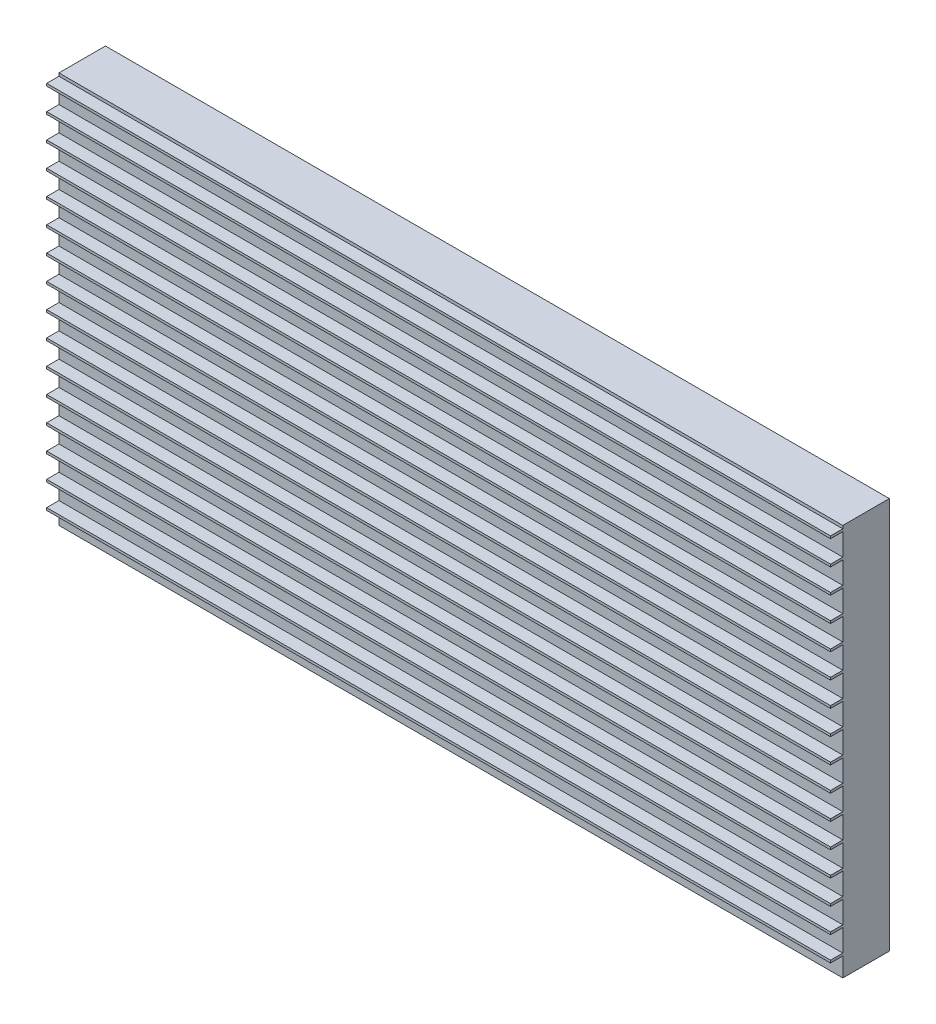
SolidWorks part; units mm, degrees
material "ABS"
ref_plane "Front Plane" through (0, 0, 0) normal (0, 0, 1) x (1, 0, 0)
ref_plane "Top Plane" through (0, 0, 0) normal (0, 1, 0) x (1, 0, 0)
ref_plane "Right Plane" through (0, 0, 0) normal (1, 0, 0) x (0, 0, -1)
sketch "Sketch1" plane through (0, 0, 0) normal (0, 0, 1) x (1, 0, 0)
  line L0 (0, 80) -> (0, 0) construction
  line L1 (-160, 80) -> (160, 80)
  line L2 (-160, 80) -> (-160, -80)
  line L3 (-160, -80) -> (160, -80)
  line L4 (160, 80) -> (160, -80)
  line L5 (0, 0) -> (0, -80) construction
  dimension "D1" = 320
  dimension "D2" = 160
extrude "Boss-Extrude1" add sketch "Sketch1" along normal blind 19
sketch "Sketch2" plane through (0, 0, 19) normal (0, 0, 1) x (1, 0, 0)
  line L0 (-155, 80) -> (-155, 75) construction
  line L1 (160, 80) -> (-160, 80) construction
  line L2 (-155, 75) -> (-160, 75) construction
  line L3 (-160, 80) -> (-160, -80) construction
  circle A0 centre (-155, 75) radius 2.5
  dimension "D1" = 5
  dimension "D2" = 5
extrude "Boss-Extrude2" [suppressed] add sketch "Sketch2" along normal blind 5
fillet "Fillet1" [suppressed] radius 2.5
pattern_linear "LPattern1" [suppressed] count 32 spacing 10 count 16 spacing 10
sketch "Sketch4" plane through (0, 0, 19) normal (0, 0, 1) x (1, 0, 0)
  line L0 (-160, 80) -> (-160, -80) construction
  line L1 (-160, 78.8) -> (160, 78.8)
  line L2 (-160, 78.8) -> (-160, 77.8)
  line L3 (-160, 77.8) -> (160, 77.8)
  line L4 (160, 78.8) -> (160, 77.8)
  line L5 (160, -80) -> (160, 80) construction
  line L6 (160, 80) -> (-160, 80) construction
  dimension "D1" = 1
  dimension "D2" = 1.2
extrude "Boss-Extrude4" add sketch "Sketch4" along normal blind 5
pattern_linear "LPattern2" count 16 spacing 10 along (0, -1, 0) of "Boss-Extrude4"
sketch "Sketch3" plane through (0, 0, 0) normal (0, 0, -1) x (-1, 0, 0)
  line L0 (-160, -80) -> (-160, 80) construction
  line L1 (-146.5, 40) -> (146.5, 40) construction
  line L2 (-146.5, 40) -> (-146.5, -40) construction
  line L3 (-146.5, -40) -> (146.5, -40) construction
  line L4 (146.5, 40) -> (146.5, -40) construction
  line L5 (0, 40) -> (0, 0) construction
  line L6 (0, 0) -> (0, -40) construction
  circle A0 centre (-146.5, 40) radius 1.5
  circle A1 centre (-146.5, -40) radius 1.5
  circle A2 centre (146.5, 40) radius 1.5
  circle A3 centre (146.5, -40) radius 1.5
  dimension "D1" = 3
  dimension "D2" = 80
  dimension "D3" = 13.5
extrude "Boss-Extrude3" [suppressed] add sketch "Sketch3" along normal blind 5
sketch "Sketch5" plane through (0, 0, 0) normal (0, 0, -1) x (-1, 0, 0)
  line L0 (-5, 0) -> (0, 0) construction
  line L1 (-140, 60) -> (-5, 60)
  line L2 (-140, 60) -> (-140, -60)
  line L3 (-140, -60) -> (-5, -60)
  line L4 (-5, 60) -> (-5, -60)
  line L5 (5, 60) -> (140, 60)
  line L6 (5, 60) -> (5, -60)
  line L7 (5, -60) -> (140, -60)
  line L8 (140, 60) -> (140, -60)
  line L9 (0, 0) -> (5, 0) construction
  dimension "D1" = 120
  dimension "D2" = 135
  dimension "D3" = 20
extrude "Cut-Extrude1" cut sketch "Sketch5" against normal blind 12
sketch "Sketch6" plane through (0, 0, 0) normal (0, 0, -1) x (-1, 0, 0)
  line L0 (0, 0) -> (0, 66.25) construction
  line L1 (-143.75, 50) -> (143.75, 50) construction
  line L2 (-143.75, 50) -> (-143.75, -50) construction
  line L3 (-143.75, -50) -> (143.75, -50) construction
  line L4 (143.75, 50) -> (143.75, -50) construction
  line L5 (0, 0) -> (0, -66.25) construction
  line L6 (-143.75, 0) -> (0, 0) construction
  line L7 (143.75, 0) -> (0, 0) construction
  line L8 (0, 66.25) -> (0, 80) construction
  line L9 (-160, 80) -> (160, 80) construction
  line L11 (-160, -80) -> (-160, 80) construction
  line L12 (-143.75, 50) -> (-140, 50) construction
  line L13 (-140, 60) -> (-140, -60) construction
  line L14 (0, -66.25) -> (0, -80) construction
  line L15 (160, -80) -> (-160, -80) construction
  line L16 (-143.75, -50) -> (-160, -50) construction
  circle A0 centre (-143.75, 50) radius 2
  circle A1 centre (-143.75, -50) radius 2
  circle A2 centre (0, 66.25) radius 2
  circle A3 centre (143.75, 50) radius 2
  circle A4 centre (143.75, -50) radius 2
  circle A5 centre (0, -66.25) radius 2
  dimension "D1" = 4
  dimension "D2" = 100
  dimension "D3" = 132.5
  dimension "D4" = 16.25
  dimension "D5" = 16.25
  dimension "D6" = 287.5
extrude "Cut-Extrude2" cut sketch "Sketch6" against normal blind 12
sketch "Sketch7" plane through (0, 0, 0) normal (0, 0, -1) x (-1, 0, 0)
  line L0 (0, 66) -> (0, 0) construction
  line L1 (-120, 66) -> (120, 66) construction
  line L2 (-120, 66) -> (-120, -66) construction
  line L3 (-120, -66) -> (120, -66) construction
  line L4 (120, 66) -> (120, -66) construction
  line L5 (0, 0) -> (0, -66) construction
  line L6 (160, -80) -> (-160, -80) construction
  line L7 (-160, -80) -> (-160, 80) construction
  circle A0 centre (-120, 66) radius 1.5
  circle A1 centre (120, 66) radius 1.5
  circle A2 centre (120, -66) radius 1.5
  circle A3 centre (-120, -66) radius 1.5
  dimension "D3" = 3
  dimension "D1" = 14
  dimension "D2" = 40
extrude "Boss-Extrude5" add sketch "Sketch7" along normal blind 4
fillet "Fillet2" radius 1.5 4 edges at (-121.5, 66, -4) (-121.5, -66, -4) (118.5, -66, -4) (118.5, 66, -4)
